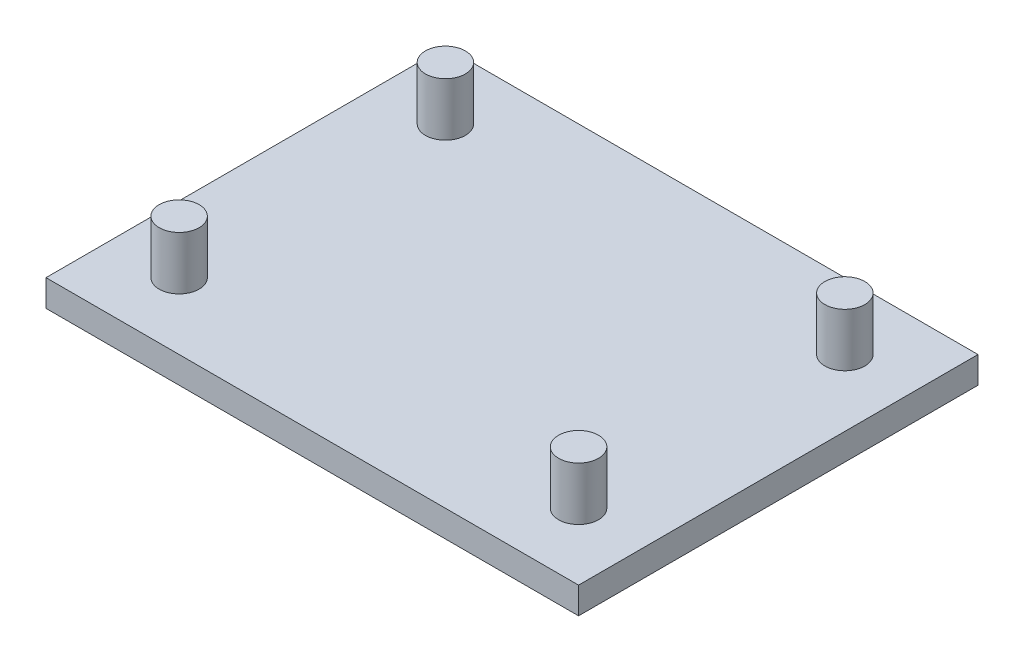
SolidWorks part; units mm, degrees
material "AISI 1020"
ref_plane "Front Plane" through (0, 0, 0) normal (0, 0, 1) x (1, 0, 0)
ref_plane "Top Plane" through (0, 0, 0) normal (0, 1, 0) x (1, 0, 0)
ref_plane "Right Plane" through (0, 0, 0) normal (1, 0, 0) x (0, 0, -1)
sketch "Sketch1" plane through (0, 0, 0) normal (0, 1, 0) x (1, 0, 0)
  line L1 (-100, -75) -> (100, -75)
  line L2 (-100, -75) -> (-100, 75)
  line L3 (-100, 75) -> (100, 75)
  line L4 (100, -75) -> (100, 75)
  line L5 (-100, -75) -> (100, 75) construction
  line L6 (-100, 75) -> (100, -75) construction
  point P0 (0, 0)
  dimension "D1" = 200
  dimension "D2" = 150
extrude "Boss-Extrude1" add sketch "Sketch1" along normal blind 10
sketch "Sketch2" plane through (0, 10, 0) normal (0, 1, 0) x (1, 0, 0)
  line L1 (-75, -50) -> (75, -50) construction
  line L2 (-75, -50) -> (-75, 50) construction
  line L3 (-75, 50) -> (75, 50) construction
  line L4 (75, -50) -> (75, 50) construction
  line L5 (-75, -50) -> (75, 50) construction
  line L6 (-75, 50) -> (75, -50) construction
  circle A0 centre (75, 50) radius 7.5
  circle A1 centre (75, -50) radius 7.5
  circle A2 centre (-75, -50) radius 7.5
  circle A3 centre (-75, 50) radius 7.5
  point P0 (0, 0)
  dimension "D1" = 15
  dimension "D2" = 150
  dimension "D3" = 100
extrude "Boss-Extrude2" add sketch "Sketch2" along normal blind 20
